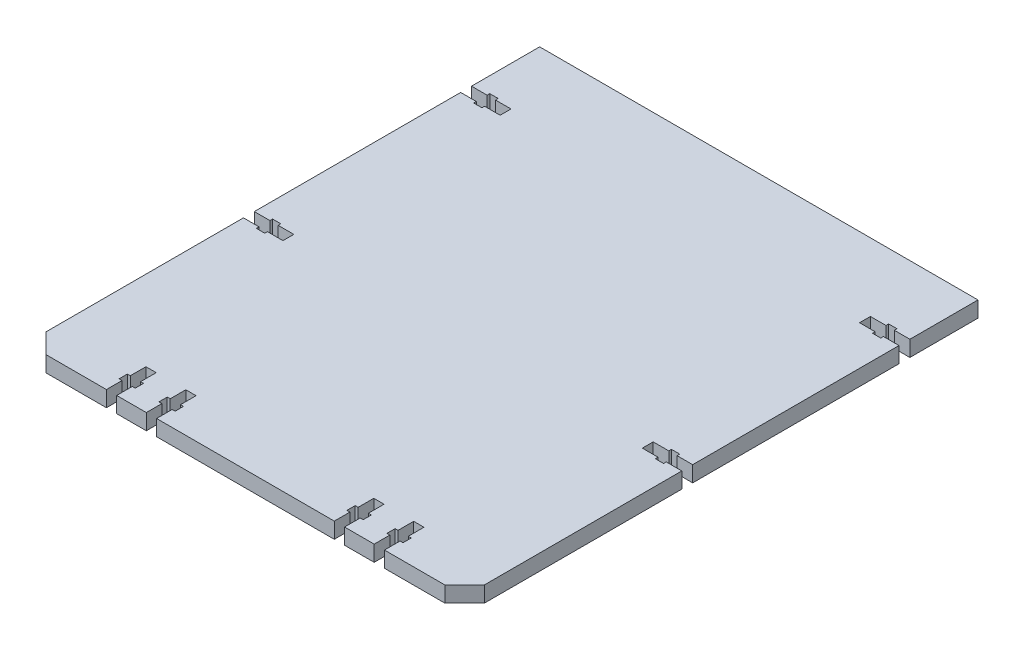
SolidWorks part; units mm, degrees
ref_plane "Спереди" through (0, 0, 0) normal (0, 0, 1) x (1, 0, 0)
ref_plane "Сверху" through (0, 0, 0) normal (0, 1, 0) x (1, 0, 0)
ref_plane "Справа" through (0, 0, 0) normal (1, 0, 0) x (0, 0, -1)
sketch "Эскиз2" plane through (0, 0, 0) normal (0, 1, 0) x (1, 0, 0)
  line L0 (-111, 0) -> (-111, 260)
  line L1 (-111, 0) -> (111, 0)
  line L2 (-111, 260) -> (111, 260)
  line L4 (111, 260) -> (111, 0)
  line L6 (-70.4, 0) -> (-70.4, 7.9)
  line L7 (-70.4, 7.9) -> (-71.9, 7.9)
  line L8 (-71.9, 7.9) -> (-71.9, 12.1)
  line L9 (-71.9, 12.1) -> (-70.4, 12.1)
  line L10 (-63.7, 12.1) -> (-63.7, 7.9)
  line L11 (-63.7, 7.9) -> (-65.2, 7.9)
  line L12 (-65.2, 7.9) -> (-65.2, 0)
  line L14 (0, 0) -> (0, 260) construction
  line L22 (-111, 225.5) -> (-103.1, 225.5)
  line L23 (-103.1, 225.5) -> (-103.1, 226.85)
  line L24 (-103.1, 226.85) -> (-98.9, 226.85)
  line L25 (-98.9, 226.85) -> (-98.9, 225.5)
  line L26 (-98.9, 218.65) -> (-103.1, 218.65)
  line L27 (-103.1, 218.65) -> (-103.1, 220)
  line L28 (-103.1, 220) -> (-111, 220)
  line L29 (-111, 115.5) -> (-103.1, 115.5)
  line L30 (-103.1, 115.5) -> (-103.1, 116.85)
  line L31 (-103.1, 116.85) -> (-98.9, 116.85)
  line L32 (-98.9, 116.85) -> (-98.9, 115.5)
  line L33 (-98.9, 108.65) -> (-103.1, 108.65)
  line L34 (-103.1, 108.65) -> (-103.1, 110)
  line L35 (-103.1, 110) -> (-111, 110)
  line L36 (-98.9, 225.5) -> (-91, 225.5)
  line L37 (-91, 225.5) -> (-91, 220)
  line L38 (-91, 220) -> (-98.9, 220)
  line L39 (-98.9, 220) -> (-98.9, 218.65)
  line L40 (98.9, 110) -> (98.9, 108.65)
  line L41 (91, 110) -> (98.9, 110)
  line L42 (91, 115.5) -> (91, 110)
  line L43 (98.9, 115.5) -> (91, 115.5)
  line L44 (98.9, 220) -> (98.9, 218.65)
  line L45 (91, 220) -> (98.9, 220)
  line L46 (91, 225.5) -> (91, 220)
  line L47 (98.9, 225.5) -> (91, 225.5)
  line L48 (103.1, 110) -> (111, 110)
  line L49 (103.1, 108.65) -> (103.1, 110)
  line L50 (98.9, 108.65) -> (103.1, 108.65)
  line L51 (98.9, 116.85) -> (98.9, 115.5)
  line L52 (103.1, 116.85) -> (98.9, 116.85)
  line L53 (-98.9, 115.5) -> (-91, 115.5)
  line L54 (-91, 115.5) -> (-91, 110)
  line L55 (-91, 110) -> (-98.9, 110)
  line L56 (103.1, 115.5) -> (103.1, 116.85)
  line L57 (111, 115.5) -> (103.1, 115.5)
  line L58 (103.1, 220) -> (111, 220)
  line L59 (103.1, 218.65) -> (103.1, 220)
  line L60 (98.9, 218.65) -> (103.1, 218.65)
  line L61 (98.9, 226.85) -> (98.9, 225.5)
  line L62 (-70.4, 12.1) -> (-70.4, 20)
  line L63 (-70.4, 20) -> (-65.2, 20)
  line L64 (-65.2, 20) -> (-65.2, 12.1)
  line L68 (-65.2, 12.1) -> (-63.7, 12.1)
  line L70 (103.1, 226.85) -> (98.9, 226.85)
  line L71 (-98.9, 110) -> (-98.9, 108.65)
  line L72 (103.1, 225.5) -> (103.1, 226.85)
  line L73 (111, 225.5) -> (103.1, 225.5)
  line L77 (-50.2, 0) -> (-50.2, 7.9)
  line L78 (-50.2, 7.9) -> (-51.7, 7.9)
  line L79 (-51.7, 7.9) -> (-51.7, 12.1)
  line L80 (-51.7, 12.1) -> (-50.2, 12.1)
  line L81 (-43.5, 12.1) -> (-43.5, 7.9)
  line L82 (-43.5, 7.9) -> (-45, 7.9)
  line L83 (-45, 7.9) -> (-45, 0)
  line L85 (-50.2, 12.1) -> (-50.2, 20)
  line L86 (-50.2, 20) -> (-45, 20)
  line L87 (-45, 20) -> (-45, 12.1)
  line L88 (-45, 12.1) -> (-43.5, 12.1)
  line L89 (45, 12.1) -> (43.5, 12.1)
  line L90 (45, 20) -> (45, 12.1)
  line L91 (50.2, 20) -> (45, 20)
  line L92 (50.2, 12.1) -> (50.2, 20)
  line L94 (45, 7.9) -> (45, 0)
  line L95 (43.5, 7.9) -> (45, 7.9)
  line L96 (43.5, 12.1) -> (43.5, 7.9)
  line L97 (51.7, 12.1) -> (50.2, 12.1)
  line L98 (51.7, 7.9) -> (51.7, 12.1)
  line L99 (50.2, 7.9) -> (51.7, 7.9)
  line L100 (50.2, 0) -> (50.2, 7.9)
  line L102 (65.2, 12.1) -> (63.7, 12.1)
  line L103 (65.2, 20) -> (65.2, 12.1)
  line L104 (70.4, 20) -> (65.2, 20)
  line L105 (70.4, 12.1) -> (70.4, 20)
  line L107 (65.2, 7.9) -> (65.2, 0)
  line L108 (63.7, 7.9) -> (65.2, 7.9)
  line L109 (63.7, 12.1) -> (63.7, 7.9)
  line L110 (71.9, 12.1) -> (70.4, 12.1)
  line L111 (71.9, 7.9) -> (71.9, 12.1)
  line L112 (70.4, 7.9) -> (71.9, 7.9)
  line L113 (70.4, 0) -> (70.4, 7.9)
  point P2 (0, 0)
  point P3 (0, 0)
  point P4 (0, 0)
  point P6 (0, 0)
  point P7 (0, 0)
  point P9 (0, 0)
  point P20 (-94.95, 110)
  point P22 (3.9943, 30)
  point P23 (0, 0)
  point P61 (-65.2, 3.95)
  dimension "D1" = 260
  dimension "D2" = 5.2
  dimension "D3" = 2
  dimension "D4" = 2
  dimension "D5" = 110
  dimension "D6" = 110
  dimension "D7" = 5.5
  dimension "D8" = 7.9
  dimension "D9" = 4.2
  dimension "D10" = 7.9
  dimension "D11" = 8.2
  dimension "D12" = 15
  dimension "D13" = 45
  dimension "D14" = 8.2
  dimension "D15" = 4.2
  dimension "D16" = 7.9
  dimension "D17" = 222
extrude "Бобышка-Вытянуть1" add sketch "Эскиз2" along normal blind 8 contours L14 L1 L94 L95 L96 L89 L90 L91 L92 L97 L98 L99 L100 L107 L108 L109 L102 L103 L104 L105 L110 L111 L112 L113 L4 L48 L49 L50 L40 L41 L42 L43 L51 L52 L56 L57 L58 L59 L60 L44 L45 L46 L47 L61 L70 L72 L73 | L1 L14 L2 L0 L22 L23 L24 L25 L36 L37 L38 L39 L26 L27 L28 L29 L30 L31 L32 L53 L54 L55 L71 L33 L34 L35 L6 L7 L8 L9 L62 L63 L64 L68 L10 L11 L12 L77 L78 L79 L80 L85 L86 L87 L88 L81 L82
chamfer "Фаска1" distance 10 angle 45 2 edges at (111, 4, 0) (-111, 4, 0)
